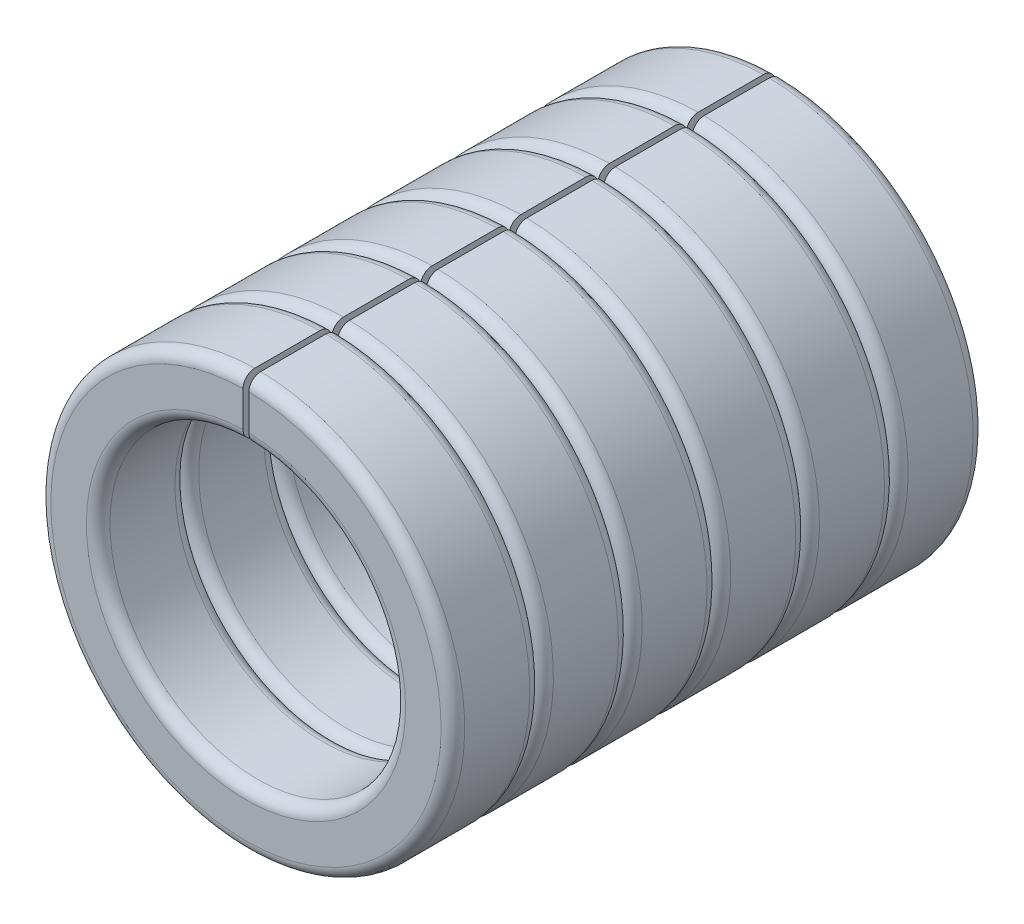
SolidWorks part; units mm, degrees
material "A-Glass Fiber"
ref_plane "Front Plane" through (0, 0, 0) normal (0, 0, 1) x (1, 0, 0)
ref_plane "Top Plane" through (0, 0, 0) normal (0, 1, 0) x (1, 0, 0)
ref_plane "Right Plane" through (0, 0, 0) normal (1, 0, 0) x (0, 0, -1)
sketch "Sketch2" plane through (0, 0, 0) normal (0, 1, 0) x (1, 0, 0)
  line L0 (0, 0) -> (0, 55.4551) construction
  line L1 (-27, 0.7) -> (-33, 0.7)
  line L2 (-25, 2.7) -> (-25, 13.7)
  line L3 (-27, 15.7) -> (-33, 15.7)
  line L4 (-35, 2.7) -> (-35, 13.7)
  line L5 (-25, 0.7) -> (-35, 15.7) construction
  line L6 (-25, 15.7) -> (-35, 0.7) construction
  arc A0 (-25, 13.7) -> (-27, 15.7) centre (-27, 13.7) ccw
  arc A1 (-27, 0.7) -> (-25, 2.7) centre (-27, 2.7) ccw
  arc A2 (-33, 0.7) -> (-35, 2.7) centre (-33, 2.7) cw
  arc A3 (-33, 15.7) -> (-35, 13.7) centre (-33, 13.7) ccw
  point P0 (-30, 8.2)
  dimension "D4" = 2
  dimension "D1" = 10
  dimension "D2" = 15
  dimension "D3" = 25
revolve "Revolve1" add sketch "Sketch2" angle 360 about L0
sketch "Sketch3" plane through (0, 0, -0.7) normal (0, 0, 1) x (1, 0, 0)
  line L1 (0.5, -0.9445) -> (-0.5, -0.9445)
  line L2 (0.5, -0.9445) -> (0.5, 75.1933)
  line L3 (0.5, 75.1933) -> (-0.5, 75.1933)
  line L4 (-0.5, -0.9445) -> (-0.5, 75.1933)
  line L5 (0.5, -0.9445) -> (-0.5, 75.1933) construction
  line L6 (0.5, 75.1933) -> (-0.5, -0.9445) construction
  point P0 (0, 37.1244)
  dimension "D1" = 1
extrude "Cut-Extrude1" cut sketch "Sketch3" against normal blind 20
pattern_linear "LPattern1" count 7 spacing 15 along (0, 0, -1) skipping (6, 0) of "Revolve1", "Cut-Extrude1"
